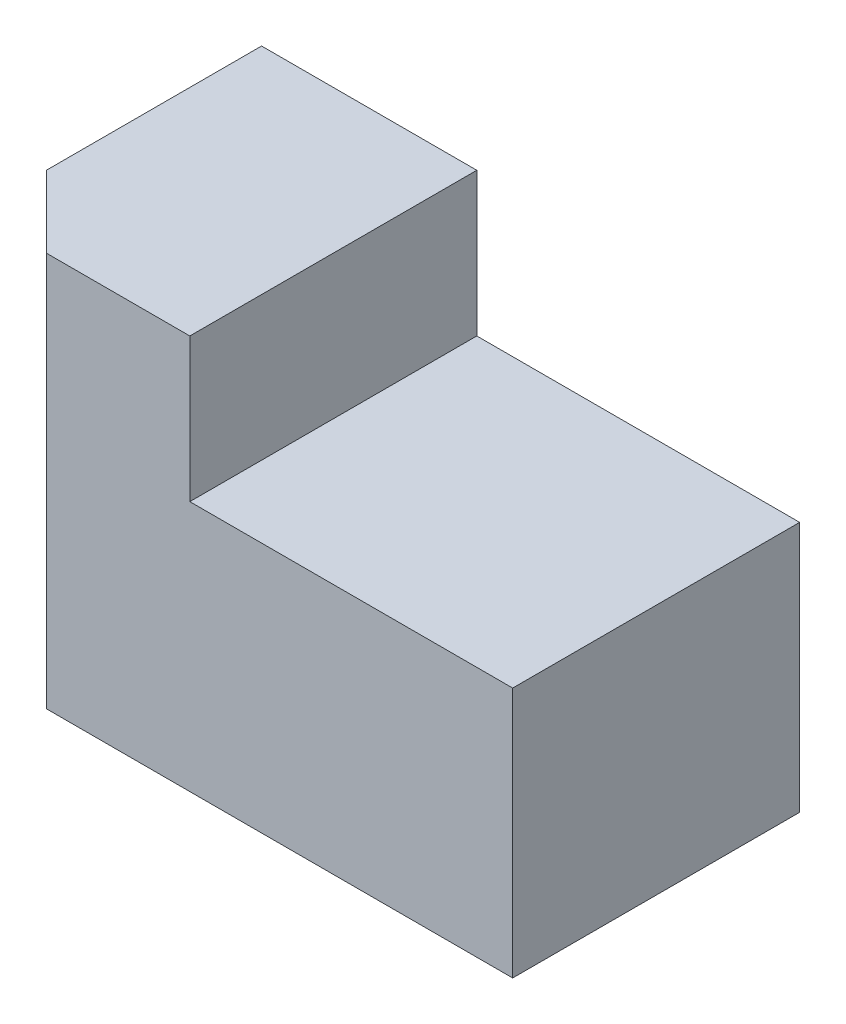
SolidWorks part; units mm, degrees
ref_plane "Front Plane" through (0, 0, 0) normal (0, 0, 1) x (1, 0, 0)
ref_plane "Top Plane" through (0, 0, 0) normal (0, 1, 0) x (1, 0, 0)
ref_plane "Right Plane" through (0, 0, 0) normal (1, 0, 0) x (0, 0, -1)
sketch "Sketch1" plane through (0, 0, 0) normal (0, 1, 0) x (1, 0, 0)
  line L0 (0, 0) -> (0, 38.1)
  line L1 (0, 38.1) -> (38.1, 38.1)
  line L2 (38.1, 38.1) -> (38.1, -12.7)
  line L5 (12.7, -12.7) -> (0, 0)
  line L6 (12.7, -12.7) -> (38.1, -12.7)
extrude "Boss-Extrude1" add sketch "Sketch1" along normal blind 69.85
sketch "Sketch2" plane through (38.1, 0, 0) normal (1, 0, 0) x (0, 0, -1)
  line L0 (38.1, 69.85) -> (38.1, 0) construction
  line L1 (-12.7, 0) -> (38.1, 0)
  line L2 (-12.7, 0) -> (-12.7, 44.45)
  line L3 (-12.7, 44.45) -> (38.1, 44.45)
  line L4 (38.1, 0) -> (38.1, 44.45)
extrude "Boss-Extrude2" add sketch "Sketch2" along normal blind 57.15
sketch "Sketch3" plane through (0, 0, 0) normal (0, -1, 0) x (-1, 0, 0)
  line L0 (0, 38.1) -> (0, 0) construction
  line L1 (-12.7, -12.7) -> (-95.25, -12.7) construction
  line L3 (-50.8, -6.35) -> (-57.15, -6.35)
  line L4 (-25.4, -6.35) -> (-31.75, -6.35)
  line L5 (-25.4, -6.35) -> (-25.4, 31.75)
  line L6 (-25.4, 31.75) -> (-31.75, 31.75)
  line L7 (-31.75, -6.35) -> (-31.75, 31.75)
  line L8 (-38.1, -6.35) -> (-44.45, -6.35)
  line L9 (-38.1, -6.35) -> (-38.1, 31.75)
  line L10 (-38.1, 31.75) -> (-44.45, 31.75)
  line L11 (-44.45, -6.35) -> (-44.45, 31.75)
  line L12 (-50.8, -6.35) -> (-50.8, 31.75)
  line L13 (-50.8, 31.75) -> (-57.15, 31.75)
  line L14 (-57.15, -6.35) -> (-57.15, 31.75)
  line L15 (-63.5, -6.35) -> (-69.85, -6.35)
  line L16 (-63.5, -6.35) -> (-63.5, 31.75)
  line L17 (-63.5, 31.75) -> (-69.85, 31.75)
  line L18 (-69.85, -6.35) -> (-69.85, 31.75)
  line L19 (-76.2, -6.35) -> (-82.55, -6.35)
  line L20 (-76.2, -6.35) -> (-76.2, 31.75)
  line L21 (-76.2, 31.75) -> (-82.55, 31.75)
  line L22 (-82.55, -6.35) -> (-82.55, 31.75)
  dimension "D1" = 38.1
  dimension "D2" = 6.35
  dimension "D3" = 25.4
  dimension "D4" = 6.35
  dimension "D5" = 6.35
  dimension "D6" = 6.35
  dimension "D7" = 6.35
  dimension "D8" = 6.35
  dimension "D9" = 6.35
  dimension "D10" = 6.35
  dimension "D11" = 6.35
  dimension "D12" = 6.35
extrude "Boss-Extrude3" add sketch "Sketch3" along normal blind 6.35
